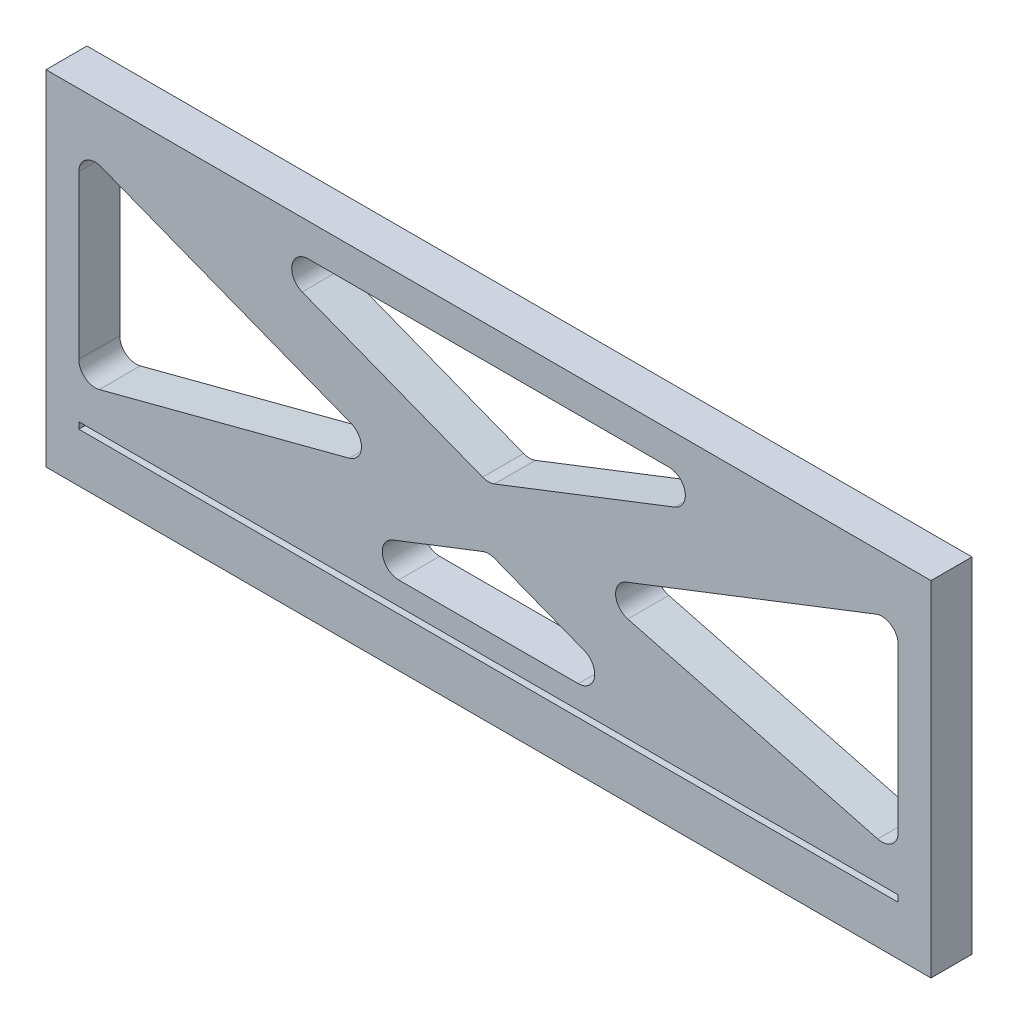
SolidWorks part; units mm, degrees
ref_plane "Front Plane" through (0, 0, 0) normal (0, 0, 1) x (1, 0, 0)
ref_plane "Top Plane" through (0, 0, 0) normal (0, 1, 0) x (1, 0, 0)
ref_plane "Right Plane" through (0, 0, 0) normal (1, 0, 0) x (0, 0, -1)
sketch "Sketch1" plane through (0, 0, 0) normal (0, 0, 1) x (1, 0, 0)
  line L0 (-20.7506, 10.795) -> (0, 2.7253)
  line L1 (-34.29, -13.335) -> (34.29, -13.335)
  line L2 (-34.29, -13.335) -> (-34.29, 13.335)
  line L3 (-34.29, 13.335) -> (34.29, 13.335)
  line L4 (34.29, -13.335) -> (34.29, 13.335)
  line L5 (-34.29, -13.335) -> (34.29, 13.335) construction
  line L6 (-34.29, 13.335) -> (34.29, -13.335) construction
  line L7 (-31.75, -9.525) -> (31.75, -9.525)
  line L8 (-31.75, -9.525) -> (-31.75, -9.025)
  line L9 (-31.75, -9.025) -> (31.75, -9.025)
  line L10 (31.75, -9.525) -> (31.75, -9.025)
  line L11 (-31.75, -9.525) -> (31.75, -9.025) construction
  line L12 (-31.75, -9.025) -> (31.75, -9.525) construction
  line L13 (0, 2.7253) -> (20.7506, 10.795)
  line L14 (20.7506, 10.795) -> (-20.7506, 10.795)
  line L15 (0, 0) -> (0, 2.7253) construction
  line L16 (-10.3753, 6.7602) -> (-11.2959, 4.3929) construction
  line L17 (10.3753, 6.7602) -> (11.2959, 4.3929) construction
  line L18 (0, 10.795) -> (0, 13.335) construction
  line L19 (-31.75, 9.6219) -> (-31.75, -6.485)
  line L20 (-31.75, -6.485) -> (-7.0079, 0)
  line L21 (-7.0079, 0) -> (-31.75, 9.6219)
  line L22 (7.0079, 0) -> (-7.0079, 0) construction
  line L23 (-19.379, 4.811) -> (-18.4584, 7.1782) construction
  line L24 (7.0079, 0) -> (31.75, 9.6219)
  line L25 (31.75, 9.6219) -> (31.75, -6.485)
  line L26 (31.75, -6.485) -> (7.0079, 0)
  line L27 (0, -1.9077) -> (-13.7296, -7.247)
  line L28 (-13.7296, -7.247) -> (13.7296, -7.247)
  line L29 (13.7296, -7.247) -> (0, -1.9077)
  line L30 (0, -1.9077) -> (0, 0) construction
  line L31 (-6.8648, -4.5774) -> (-7.5092, -2.9203) construction
  line L32 (6.8648, -4.5774) -> (7.5092, -2.9203) construction
  line L33 (0, -7.247) -> (0, -9.025) construction
  point P0 (0, 0)
  point P6 (0, -9.275)
  point P27 (0, 0)
  dimension "D1" = 3.81
  dimension "D2" = 2.54
  dimension "D3" = 68.58
  dimension "D4" = 26.67
  dimension "D5" = 0.5
  dimension "D6" = 2.54
  dimension "D7" = 2.54
  dimension "D8" = 2.54
  dimension "D9" = 1.778
extrude "Boss-Extrude1" add sketch "Sketch1" along normal blind 3.175
fillet "Fillet1" radius 1.27 12 edges at (31.75, 9.6219, 1.5875) (31.75, -6.485, 1.5875) (7.0079, 0, 1.5875) (20.7506, 10.795, 1.5875) (-20.7506, 10.795, 1.5875) (0, 2.7253, 1.5875) (-7.0079, 0, 1.5875) (-31.75, 9.6219, 1.5875) (-31.75, -6.485, 1.5875) (13.7296, -7.247, 1.5875) (0, -1.9077, 1.5875) (-13.7296, -7.247, 1.5875)
